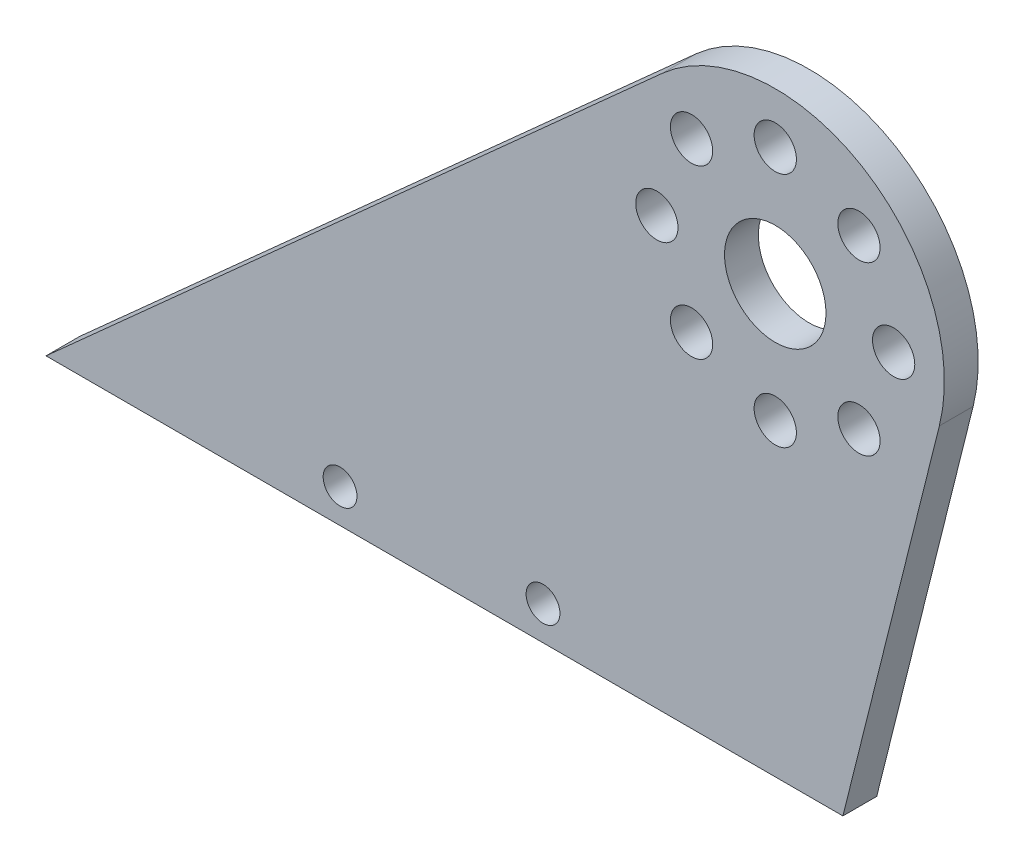
SolidWorks part; units mm, degrees
material "自訂玻璃纖維"
ref_plane "前基準面" through (0, 0, 0) normal (0, 0, 1) x (1, 0, 0)
ref_plane "上基準面" through (0, 0, 0) normal (0, 1, 0) x (1, 0, 0)
ref_plane "右基準面" through (0, 0, 0) normal (1, 0, 0) x (0, 0, -1)
sketch "草圖1" plane through (0, 0, 0) normal (0, 0, 1) x (1, 0, 0)
  line L0 (-41.0787, -25.2469) -> (3.125, -25.2469)
  line L1 (-6.6774, 7.4439) -> (-43.1207, -25.2469)
  line L2 (4.0001, -25.2469) -> (9.7018, -2.4238)
  line L4 (-43.1207, -25.2469) -> (-41.0787, -25.2469)
  line L6 (4.0001, -25.2469) -> (3.125, -25.2469)
  arc A0 (9.7018, -2.4238) -> (-6.6774, 7.4439) centre (0, 0) ccw
  circle A1 centre (0, 0) radius 3
  circle A2 centre (0, 7) radius 1.25
  circle A3 centre (4.9497, 4.9497) radius 1.25
  circle A4 centre (7, 0) radius 1.25
  circle A5 centre (4.9497, -4.9497) radius 1.25
  circle A6 centre (0, -7) radius 1.25
  circle A7 centre (-4.9497, -4.9497) radius 1.25
  circle A8 centre (-7, 0) radius 1.25
  circle A9 centre (-4.9497, 4.9497) radius 1.25
  circle A13 centre (-13.7326, -23.2469) radius 1
  circle A14 centre (-25.7326, -23.2469) radius 1
  point P22 (0, 0)
  point P25 (3.9807, -25.2469)
  dimension "D1" = 20
  dimension "D2" = 6
  dimension "D3" = 2.5
  dimension "D4" = 7
  dimension "D8" = 12
extrude "填料-伸長1" add sketch "草圖1" along normal blind 2
